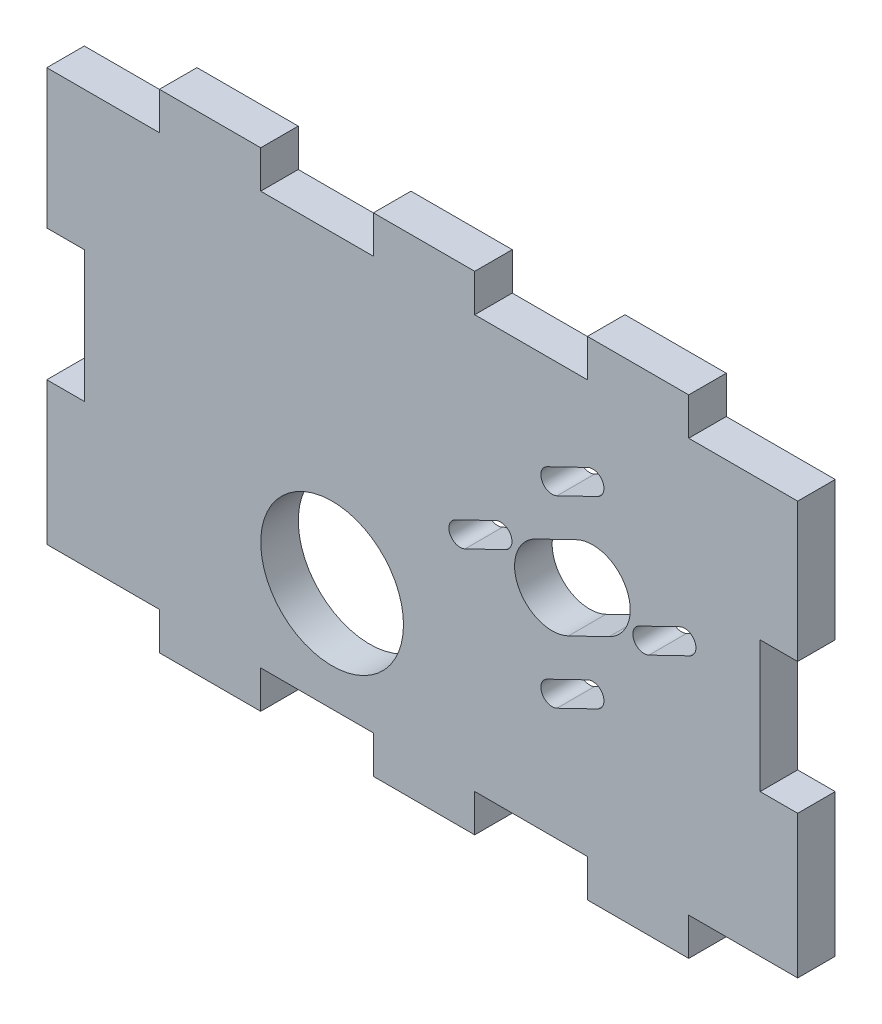
SolidWorks part; units mm, degrees
material "Acrylique (impact moyen-haut)"
ref_plane "Plan de face" through (0, 0, 0) normal (0, 0, 1) x (1, 0, 0)
ref_plane "Plan de dessus" through (0, 0, 0) normal (0, 1, 0) x (1, 0, 0)
ref_plane "Plan de droite" through (0, 0, 0) normal (1, 0, 0) x (0, 0, -1)
sketch "Esquisse1" plane through (0, 0, 0) normal (0, 0, 1) x (1, 0, 0)
  line L1 (50, -32.5) -> (-50, -32.5)
  line L2 (50, -32.5) -> (50, 32.5)
  line L3 (50, 32.5) -> (-50, 32.5)
  line L4 (-50, -32.5) -> (-50, 32.5)
  line L5 (50, -32.5) -> (-50, 32.5) construction
  line L6 (50, 32.5) -> (-50, -32.5) construction
  point P0 (0, 0)
  dimension "D1" = 100
  dimension "D2" = 65
extrude "Boss.-Extru.1" add sketch "Esquisse1" along normal blind 5
sketch "Esquisse2" plane through (0, 0, 5) normal (0, 0, 1) x (1, 0, 0)
  line L0 (50, 32.5) -> (-50, 32.5) construction
  line L1 (-50, 32.5) -> (-50, -32.5) construction
  line L2 (50, -32.5) -> (50, 32.5) construction
  line L3 (-35, 32.5) -> (-50, 32.5)
  line L4 (-35, 32.5) -> (-35, 27.49)
  line L5 (-35, 27.49) -> (-50, 27.49)
  line L6 (-50, 32.5) -> (-50, 27.49)
  line L7 (-21.51, 32.5) -> (-6.5, 32.5)
  line L8 (-21.51, 32.5) -> (-21.51, 27.49)
  line L9 (-21.51, 27.49) -> (-6.5, 27.49)
  line L10 (-6.5, 32.5) -> (-6.5, 27.49)
  line L11 (6.99, 32.5) -> (22, 32.5)
  line L12 (6.99, 32.5) -> (6.99, 27.49)
  line L13 (6.99, 27.49) -> (22, 27.49)
  line L14 (22, 32.5) -> (22, 27.49)
  line L15 (35.49, 32.5) -> (50, 32.5)
  line L16 (35.49, 32.5) -> (35.49, 27.5)
  line L17 (35.49, 27.5) -> (50, 27.5)
  line L18 (50, 32.5) -> (50, 27.5)
  line L19 (0, 32.5) -> (0, -35.188) construction
  line L20 (-50, 9) -> (-45, 9)
  line L21 (-50, 9) -> (-50, -8.5)
  line L22 (-50, -8.5) -> (-45, -8.5)
  line L23 (-45, 9) -> (-45, -8.5)
  line L24 (45, 9) -> (45, -8.5)
  line L25 (50, -8.5) -> (45, -8.5)
  line L26 (50, 9) -> (50, -8.5)
  line L27 (50, 9) -> (45, 9)
  line L28 (50.7693, 0) -> (-61.67, 0) construction
  line L29 (50, -32.5) -> (50, -27.5)
  line L30 (35.49, -27.5) -> (50, -27.5)
  line L31 (35.49, -32.5) -> (35.49, -27.5)
  line L32 (35.49, -32.5) -> (50, -32.5)
  line L33 (22, -32.5) -> (22, -27.49)
  line L34 (6.99, -27.49) -> (22, -27.49)
  line L35 (6.99, -32.5) -> (6.99, -27.49)
  line L36 (6.99, -32.5) -> (22, -32.5)
  line L37 (-6.5, -32.5) -> (-6.5, -27.49)
  line L38 (-21.51, -27.49) -> (-6.5, -27.49)
  line L39 (-21.51, -32.5) -> (-21.51, -27.49)
  line L40 (-21.51, -32.5) -> (-6.5, -32.5)
  line L41 (-50, -32.5) -> (-50, -27.49)
  line L42 (-35, -27.49) -> (-50, -27.49)
  line L43 (-35, -32.5) -> (-35, -27.49)
  line L44 (-35, -32.5) -> (-50, -32.5)
  point P0 (-35, 32.5)
  point P1 (-21.51, 32.5)
  point P6 (6.99, 32.5)
  point P7 (22, 32.5)
  point P8 (35.49, 32.5)
  point P9 (-50, 9)
  point P10 (-50, -8.5)
  point P13 (-50, 27.49)
  dimension "D1" = 15
  dimension "D2" = 13.49
  dimension "D3" = 5.01
  dimension "D4" = 43.5
  dimension "D5" = 5.01
  dimension "D6" = 13.49
  dimension "D7" = 23.5
  dimension "D8" = 17.5
  dimension "D9" = 5.01
  dimension "D10" = 5
  dimension "D11" = 72
  dimension "D12" = 13.49
extrude "Enlèv. mat.-Extru.1" cut sketch "Esquisse2" against normal blind 5
sketch "Esquisse3" plane through (0, 0, 5) normal (0, 0, 1) x (1, 0, 0)
  line L4 (-35, -32.5) -> (-21.51, -32.5) construction
  line L5 (-50, -8.5) -> (-50, -27.49) construction
  point P4 (-12, -13)
  dimension "D8" = 19.5
  dimension "D9" = 38
sketch "Esquisse7" plane through (0, 0, 5) normal (0, 0, 1) x (1, 0, 0)
  line L0 (-35, -32.5) -> (-21.51, -32.5) construction
  line L1 (-50, -8.5) -> (-50, -27.49) construction
  circle A0 centre (-12, -13) radius 9.505
  dimension "D1" = 19.01
  dimension "D2" = 19.5
  dimension "D3" = 38
extrude "Enlèv. mat.-Extru.5" cut sketch "Esquisse7" against normal blind 10
sketch "Esquisse8" plane through (0, 0, 5) normal (0, 0, 1) x (1, 0, 0)
  line L0 (50, 9) -> (50, 27.5) construction
  line L1 (20, 2.5) -> (20, -42.6961) construction
  line L2 (22, -32.5) -> (35.49, -32.5) construction
  line L3 (-12, -13) -> (20, 2.5) construction
  line L4 (22.6999, 3.8078) -> (17.3001, 1.1922) construction
  line L5 (24.8796, -0.6921) -> (19.4797, -3.3077)
  line L6 (20.5203, 8.3077) -> (15.1204, 5.6921)
  line L7 (20, 2.5) -> (20, 42.8745) construction
  line L8 (22.6999, -8.4422) -> (17.3001, -11.0578) construction
  line L9 (22.6999, 16.0578) -> (17.3001, 13.4422) construction
  line L10 (23.3538, 14.7078) -> (17.9539, 12.0922)
  line L11 (22.0461, 17.4078) -> (16.6462, 14.7922)
  line L12 (23.3538, -9.7922) -> (17.9539, -12.4078)
  line L13 (22.0461, -7.0922) -> (16.6462, -9.7078)
  line L14 (-0.7597, 2.5) -> (32.25, 2.5) construction
  line L15 (10.4499, 3.8078) -> (5.0501, 1.1922) construction
  line L16 (11.1038, 2.4578) -> (5.7039, -0.1578)
  line L17 (9.7961, 5.1578) -> (4.3962, 2.5422)
  line L18 (34.9499, 3.8078) -> (29.5501, 1.1922) construction
  line L19 (35.6038, 2.4578) -> (30.2039, -0.1578)
  line L20 (34.2961, 5.1578) -> (28.8962, 2.5422)
  line L21 (12.3001, 1.1922) -> (12.3001, -5.0254) construction
  line L22 (17.3001, -3.8078) -> (11.1038, -3.8078) construction
  line L23 (-21.505, -13) -> (-21.505, -24.2005) construction
  line L24 (-12, -22.505) -> (-24.6092, -22.505) construction
  line L25 (15.8001, 13.4422) -> (15.8001, 11.9422) construction
  line L26 (15.8001, 11.9422) -> (17.3001, 11.9422) construction
  line L27 (28.0501, 1.1922) -> (28.0501, -1.5068) construction
  line L28 (29.5501, -0.3078) -> (26.8646, -0.3078) construction
  line L29 (3.5501, 1.1922) -> (3.5501, -0.3078) construction
  line L30 (34.9499, 5.3078) -> (36.4499, 5.3078) construction
  arc A0 (24.8796, -0.6921) -> (20.5203, 8.3077) centre (22.6999, 3.8078) ccw
  arc A1 (15.1204, 5.6921) -> (19.4797, -3.3077) centre (17.3001, 1.1922) ccw
  arc A2 (23.3538, 14.7078) -> (22.0461, 17.4078) centre (22.6999, 16.0578) ccw
  arc A3 (16.6462, 14.7922) -> (17.9539, 12.0922) centre (17.3001, 13.4422) ccw
  arc A4 (23.3538, -9.7922) -> (22.0461, -7.0922) centre (22.6999, -8.4422) ccw
  arc A5 (16.6462, -9.7078) -> (17.9539, -12.4078) centre (17.3001, -11.0578) ccw
  arc A6 (11.1038, 2.4578) -> (9.7961, 5.1578) centre (10.4499, 3.8078) ccw
  arc A7 (4.3962, 2.5422) -> (5.7039, -0.1578) centre (5.0501, 1.1922) ccw
  arc A8 (35.6038, 2.4578) -> (34.2961, 5.1578) centre (34.9499, 3.8078) ccw
  arc A9 (28.8962, 2.5422) -> (30.2039, -0.1578) centre (29.5501, 1.1922) ccw
  circle A10 centre (-12, -13) radius 9.505 construction
  point P0 (20, 2.5)
  point P10 (20, 2.5)
  point P15 (20, 14.75)
  point P18 (20, -9.75)
  point P21 (20, 14.75)
  point P29 (20, -9.75)
  point P37 (7.75, 2.5)
  point P40 (7.75, 2.5)
  point P45 (32.25, 2.5)
  point P48 (32.25, 2.5)
  point P55 (12.3001, -3.8078)
  point P62 (-21.505, -22.5)
  point P67 (15.8001, 11.9422)
  point P71 (28.0501, -0.1573)
  point P74 (27.6999, 8.8078)
  point P75 (3.5501, -0.3078)
  point P76 (24.1999, 17.5578)
  point P80 (36.4499, 5.3078)
  dimension "D1" = 30
  dimension "D2" = 35
  dimension "D3" = 10
  dimension "D4" = 6
  dimension "D5" = 12.25
  dimension "D6" = 6
  dimension "D7" = 3
  dimension "D8" = 12.25
  dimension "D9" = 6
  dimension "D10" = 12.25
  dimension "D11" = 6
  dimension "D12" = 12.25
  dimension "D13" = 6
  dimension "D14" = 3
  dimension "D15" = 3
  dimension "D16" = 3
  dimension "D17" = 12.25
  dimension "D18" = 12.25
  dimension "D19" = 12.25
extrude "Enlèv. mat.-Extru.6" cut sketch "Esquisse8" against normal blind 10
